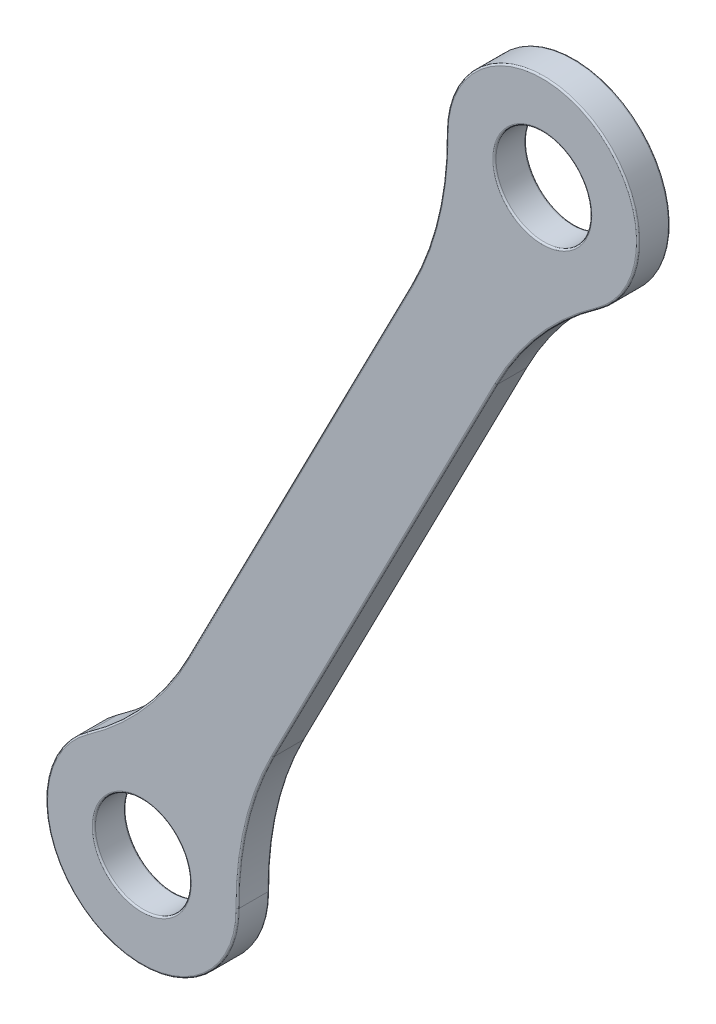
SolidWorks part; units mm, degrees
material "Plain Carbon Steel"
ref_plane "Front Plane" through (0, 0, 0) normal (0, 0, 1) x (1, 0, 0)
ref_plane "Top Plane" through (0, 0, 0) normal (0, 1, 0) x (1, 0, 0)
ref_plane "Right Plane" through (0, 0, 0) normal (1, 0, 0) x (0, 0, -1)
sketch "Sketch1" plane through (0, 0, 0) normal (0, 0, 1) x (1, 0, 0)
  line L0 (14.5, 81.5) -> (52.1117, 154.5962) construction
  line L1 (14.5, 81.5) -> (52.1117, 154.5962) construction
  line L2 (14.5, 81.5) -> (52.1117, 154.5962) construction
  line L3 (10.4986, 83.5589) -> (48.1104, 156.6551)
  line L4 (18.5014, 79.4411) -> (56.1131, 152.5373)
  circle A0 centre (14.5, 81.5) radius 9 construction
  circle A1 centre (52.1117, 154.5962) radius 9 construction
  arc A2 (10.4986, 83.5589) -> (18.5014, 79.4411) centre (14.5, 81.5) ccw
  arc A3 (56.1131, 152.5373) -> (48.1104, 156.6551) centre (52.1117, 154.5962) ccw
  arc A4 (48.1104, 156.6551) -> (56.1131, 152.5373) centre (52.1117, 154.5962) ccw
  arc A5 (44.5442, 149.7246) -> (52.547, 145.6068) centre (52.1117, 154.5962) cw
  arc A6 (10.4986, 83.5589) -> (18.5014, 79.4411) centre (14.5, 81.5) cw
  arc A7 (14.0648, 90.4895) -> (22.0675, 86.3717) centre (14.5, 81.5) ccw
  point P5 (33.3059, 118.0481)
  dimension "D1" = 18
  dimension "D2" = 9
extrude "Boss-Extrude1" add sketch "Sketch1" along normal blind 3 contours L3 A6 L4 A4 | A5 L3 A3 L4 | L3 A7 L4 A2
fillet "Fillet1" radius 30 4 edges at (44.5442, 149.7246, 1.5) (52.547, 145.6068, 1.5) (22.0675, 86.3717, 1.5) (14.0648, 90.4895, 1.5)
fillet "Fillet2" radius 0.15 20 edges at (19, 81.5, 3) (19, 81.5, 0) (56.6117, 154.5962, 3) (56.6117, 154.5962, 0) (42.3053, 147.2929, 3) (42.3053, 147.2929, 0) (56.2295, 162.599, 0) (56.2295, 162.599, 3) (51.8699, 142.3715, 3) (51.8699, 142.3715, 0) (37.3072, 115.9892, 0) (37.3072, 115.9892, 3) (24.3064, 88.8033, 3) (24.3064, 88.8033, 0) (10.3822, 73.4973, 0) (10.3822, 73.4973, 3) (14.7418, 93.7247, 3) (14.7418, 93.7247, 0) (29.3045, 120.107, 3) (29.3045, 120.107, 0)
